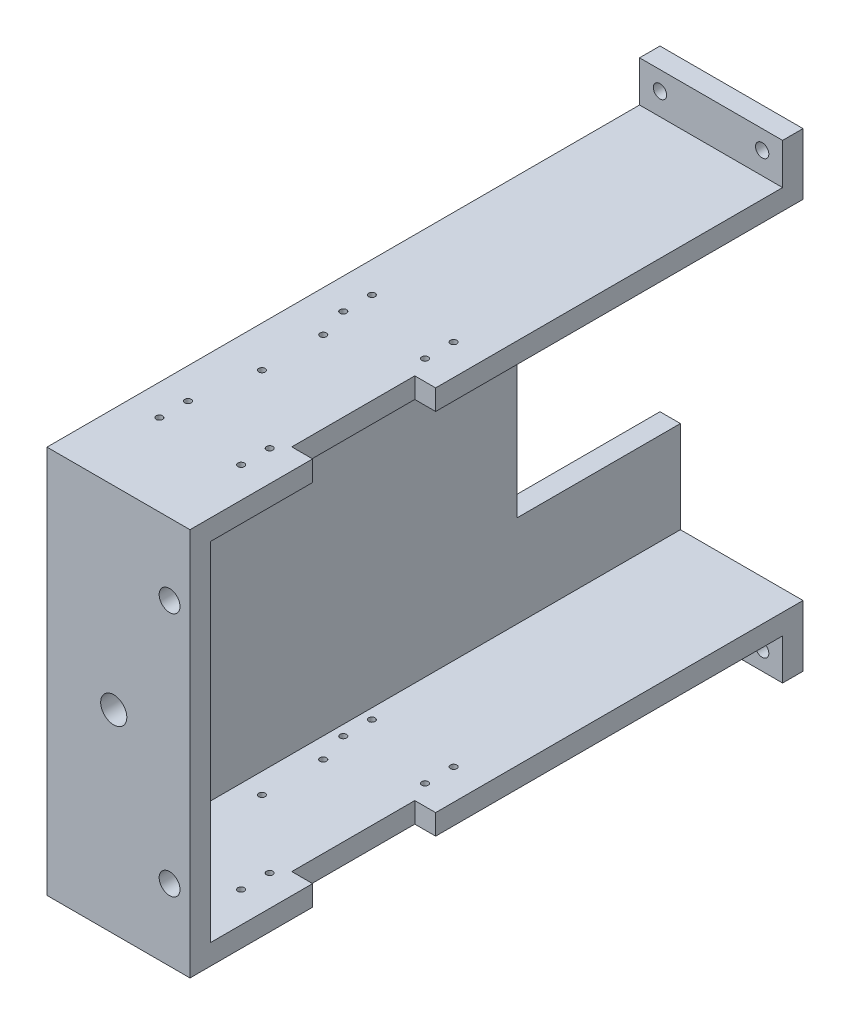
SolidWorks part; units mm, degrees
other "Markup2"
sketch "Sketch14" plane through (44.45, -152.4, 190.5) normal (0.8655, -0.4695, 0.1749) x (0.49, 0.866, -0.1002)
other "Markup3"
sketch "Sketch15" plane through (44.45, -152.4, 190.5) normal (0.8655, -0.4695, 0.1749) x (0.49, 0.866, -0.1002)
ref_plane "Front Plane" through (0, 0, 0) normal (0, 0, 1) x (1, 0, 0)
ref_plane "Top Plane" through (0, 0, 0) normal (0, 1, 0) x (1, 0, 0)
ref_plane "Right Plane" through (0, 0, 0) normal (1, 0, 0) x (0, 0, -1)
sketch "Sketch1" plane through (0, 0, 0) normal (0, 0, 1) x (1, 0, 0)
  line L0 (0, 0) -> (44.45, 0) construction
  line L5 (0, -60.325) -> (44.45, -60.325)
  line L6 (0, -60.325) -> (0, 60.325)
  line L7 (0, 60.325) -> (44.45, 60.325)
  line L8 (44.45, -60.325) -> (44.45, 60.325)
  dimension "D1" = 120.65
  dimension "D2" = 44.45
extrude "Boss-Extrude1" add sketch "Sketch1" along normal blind 190.5
sketch "Sketch2" plane through (0, 0, 0) normal (0, 0, -1) x (-1, 0, 0)
  line L0 (-44.45, -60.325) -> (-44.45, 60.325) construction
  line L1 (-6.35, -53.975) -> (-44.45, -53.975)
  line L2 (-6.35, -53.975) -> (-6.35, 53.975)
  line L3 (-6.35, 53.975) -> (-44.45, 53.975)
  line L4 (-44.45, -53.975) -> (-44.45, 53.975)
  line L5 (-6.35, -53.975) -> (-44.45, 53.975) construction
  line L6 (-6.35, 53.975) -> (-44.45, -53.975) construction
  line L7 (0, 60.325) -> (0, -60.325) construction
  line L8 (-44.45, 60.325) -> (0, 60.325) construction
  point P0 (-25.4, 0)
  dimension "D1" = 6.35
  dimension "D2" = 6.35
extrude "Cut-Extrude1" cut sketch "Sketch2" against normal offset from surface (184.15 mm away) 6.35 up to face at (22.225, 0, 190.5)
sketch "Sketch4" plane through (0, 0, 184.15) normal (0, 0, -1) x (-1, 0, 0)
  line L3 (-44.45, 0) -> (24.1169, 0) construction
  line L4 (-44.45, -53.975) -> (-44.45, 53.975) construction
  circle A0 centre (-38.1, 38.1) radius 3.2385
  circle A1 centre (-38.1, -38.1) radius 3.2385
  dimension "D3" = 6.477
  dimension "D1" = 6.35
  dimension "D2" = 76.2
extrude "Cut-Extrude4" cut sketch "Sketch4" against normal through all both
sketch "Sketch17" plane through (0, -60.325, 0) normal (0, -1, 0) x (1, 0, 0)
  line L0 (44.45, 190.5) -> (44.45, 0) construction
  line L1 (37.973, 152.4) -> (44.45, 152.4)
  line L2 (37.973, 152.4) -> (37.973, 114.173)
  line L3 (37.973, 114.173) -> (44.45, 114.173)
  line L4 (44.45, 152.4) -> (44.45, 114.173)
  line L6 (0, 0) -> (44.45, 0) construction
  point P10 (15.3177, 0)
  dimension "D3" = 6.477
  dimension "D2" = 38.227
  dimension "D1" = 114.173
extrude "Cut-Extrude5" cut sketch "Sketch17" against normal through all
sketch "Sketch18" plane through (6.35, 0, 0) normal (1, 0, 0) x (0, 0, -1)
  line L0 (0, -53.975) -> (0, 53.975) construction
  line L1 (0, 25.4) -> (-50.8, 25.4)
  line L2 (0, 25.4) -> (0, -25.4)
  line L3 (0, -25.4) -> (-50.8, -25.4)
  line L4 (-50.8, 25.4) -> (-50.8, -25.4)
  dimension "D1" = 50.8
  dimension "D2" = 50.8
extrude "Cut-Extrude6" cut sketch "Sketch18" against normal through all
sketch "Sketch19" plane through (0, -60.325, 0) normal (0, -1, 0) x (1, 0, 0)
  line L0 (0, 190.5) -> (0, 0) construction
  line L1 (0, 6.35) -> (44.45, 6.35)
  line L2 (0, 6.35) -> (0, 0)
  line L3 (0, 0) -> (44.45, 0)
  line L4 (44.45, 6.35) -> (44.45, 0)
  dimension "D1" = 6.35
extrude "Boss-Extrude2" add sketch "Sketch19" along normal blind 12.7
sketch "Sketch21" plane through (0, 0, 6.35) normal (0, 0, 1) x (1, 0, 0)
  line L0 (44.45, -73.025) -> (44.45, -60.325) construction
  circle A0 centre (6.35, -67.1976) radius 2.0635
  circle A1 centre (38.1, -67.1976) radius 2.0635
  dimension "D1" = 4.127
  dimension "D2" = 4.127
  dimension "D3" = 6.35
  dimension "D4" = 31.75
extrude "Cut-Extrude7" cut sketch "Sketch21" against normal through all
mirror "Mirror1" about plane through (0, 0, 0) normal (0, 1, 0) of "Boss-Extrude2", "Cut-Extrude7"
sketch "Sketch23" plane through (0, 0, 190.5) normal (0, 0, 1) x (1, 0, 0)
  circle A0 centre (20.75, 0) radius 4.0635
  circle A1 centre (38.1, 38.1) radius 3.2385 construction
  dimension "D2" = 8.127
  dimension "D1" = 17.35
extrude "Cut-Extrude8" cut sketch "Sketch23" against normal through all
sketch "Sketch24" plane through (0, -60.325, 0) normal (0, -1, 0) x (1, 0, 0)
  line L0 (0, 190.5) -> (0, 6.35) construction
  line L2 (37.973, 114.173) -> (44.45, 114.173) construction
  circle A0 centre (12.7, 117.348) radius 1
  circle A1 centre (12.7, 136.398) radius 1
  point P6 (0, 0)
  dimension "D2" = 2
  dimension "D3" = 2
  dimension "D1" = 12.7
  dimension "D5" = 19.05
  dimension "D4" = 3.175
extrude "Cut-Extrude9" cut sketch "Sketch24" against normal through all
sketch "Sketch25" plane through (0, -60.325, 0) normal (0, -1, 0) x (1, 0, 0)
  line L0 (0, 190.5) -> (0, 6.35) construction
  line L1 (44.45, 152.4) -> (37.973, 152.4) construction
  line L2 (0, 160.655) -> (44.45, 160.655) construction
  line L3 (44.45, 190.5) -> (44.45, 152.4) construction
  circle A0 centre (9.525, 156.21) radius 1
  circle A1 centre (34.925, 156.21) radius 1
  circle A2 centre (34.925, 165.1) radius 1
  circle A3 centre (9.525, 165.1) radius 1
  dimension "D2" = 2
  dimension "D4" = 2
  dimension "D1" = 9.525
  dimension "D3" = 3.81
  dimension "D5" = 25.4
  dimension "D6" = 4.445
extrude "Cut-Extrude10" cut sketch "Sketch25" against normal through all
pattern_linear "LPattern1" count 2 spacing 57.15 along (0, 0, -1) of "Cut-Extrude10"
equation "\"tightTol\" = 0.005in"
equation "\"normTol\"= 0.01in"
equation "\"looseTol\"= 0.02in"
equation "\"D3@Sketch4\"=\"tightTol\"+0.250000in"
equation "\"D2@Sketch17\"=1.5+\"tightTol\""
equation "\"D3@Sketch17\"=0.25+\"tightTol\""
equation "\"D1@Sketch17\"=4.5-\"tightTol\""
equation "\"D2@Sketch21\"=\"tightTol\"+0.15748031in"
equation "\"D1@Sketch21\"=\"tightTol\"+0.15748032in"
equation "\"D2@Sketch23\"=\"tightTol\"+8mm"
equation "\"D2@Sketch24\"=2mm"
equation "\"D3@Sketch24\"=2mm"
equation "\"D2@Sketch25\"=2mm"
equation "\"D4@Sketch25\"=2mm"
